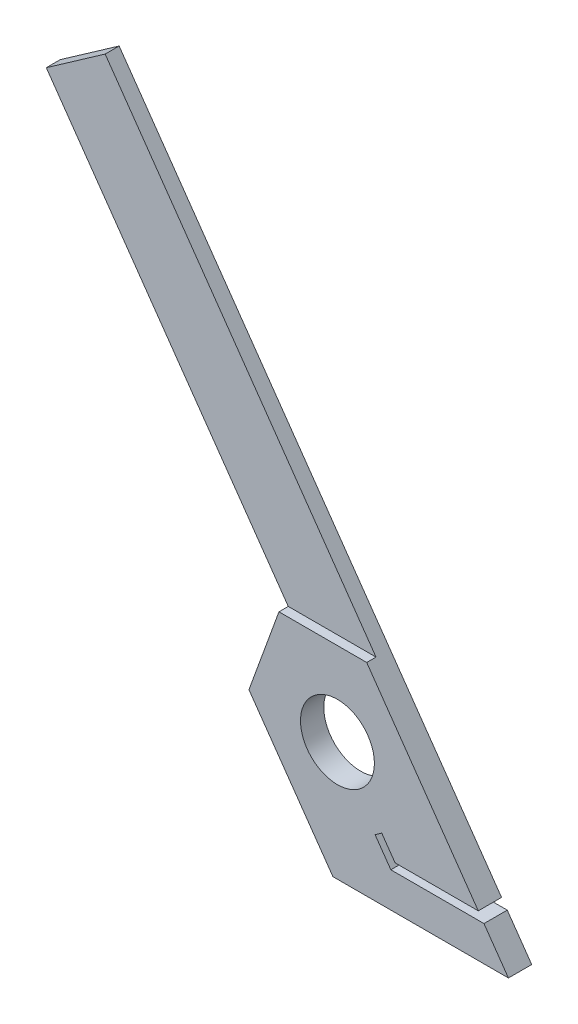
SolidWorks part; units mm, degrees
ref_plane "Front Plane" through (0, 0, 0) normal (0, 0, 1) x (1, 0, 0)
ref_plane "Top Plane" through (0, 0, 0) normal (0, 1, 0) x (1, 0, 0)
ref_plane "Right Plane" through (0, 0, 0) normal (1, 0, 0) x (0, 0, -1)
sketch "Sketch1" plane through (0, 0, 0) normal (0, 0, 1) x (1, 0, 0)
  line L0 (-0.3878, -10.212) -> (-7.6022, 0.0913)
  line L1 (-20.7527, 40.4037) -> (-25.8109, 36.8618)
  line L2 (-7.6022, 0.0913) -> (-5.024, 7.175)
  line L3 (-5.024, 7.175) -> (-25.8109, 36.8618)
  line L4 (-20.7527, 40.4037) -> (12.098, -6.512)
  line L5 (12.098, -6.512) -> (4.9526, -6.512)
  line L6 (14.6888, -10.212) -> (-0.3878, -10.212)
  line L7 (5.0583, 3.5418) -> (-5.0583, -3.5418) construction
  line L8 (4.5882, -7.212) -> (3.232, -5.2752)
  line L9 (4.5882, -7.212) -> (12.5882, -7.212)
  line L10 (3.232, -5.2752) -> (3.8054, -4.8737)
  line L11 (3.8054, -4.8737) -> (4.9526, -6.512)
  line L12 (4.9526, -6.512) -> (4.9526, -7.212) construction
  line L13 (4.9526, -6.512) -> (4.3792, -6.9135) construction
  line L14 (12.5882, -7.212) -> (14.6888, -10.212)
  circle A0 centre (0, 0) radius 3.175
  point P12 (0, 0)
  dimension "D1" = 6.35
  dimension "D6" = 45
  dimension "D3" = 3
  dimension "D5" = 4
  dimension "D10" = 3
  dimension "D2" = 55
  dimension "D4" = 125
  dimension "D7" = 0.7
  dimension "D8" = 2
  dimension "D9" = 3
  dimension "D11" = 8
extrude "Boss-Extrude1" add sketch "Sketch1" along normal blind 1.2
sketch "Sketch2" plane through (0, 0, 1.2) normal (0, 0, 1) x (1, 0, 0)
  line L0 (-5.024, 7.175) -> (2.5143, 7.175)
  line L12 (-0.3878, -10.212) -> (14.6888, -10.212)
  line L13 (14.6888, -10.212) -> (12.5882, -7.212)
  line L14 (12.5882, -7.212) -> (4.5882, -7.212)
  line L15 (4.5882, -7.212) -> (3.232, -5.2752)
  line L16 (3.232, -5.2752) -> (3.8054, -4.8737)
  line L17 (3.8054, -4.8737) -> (4.9526, -6.512)
  line L18 (4.9526, -6.512) -> (12.098, -6.512)
  line L19 (12.098, -6.512) -> (-20.7527, 40.4037)
  line L20 (-20.7527, 40.4037) -> (-25.8109, 36.8618)
  line L21 (-25.8109, 36.8618) -> (-5.024, 7.175)
  line L22 (-5.024, 7.175) -> (-7.6022, 0.0913)
  line L23 (-7.6022, 0.0913) -> (-0.3878, -10.212)
  line L24 (-0.3878, -10.212) -> (14.6888, -10.212)
  line L25 (14.6888, -10.212) -> (12.5882, -7.212)
  line L26 (12.5882, -7.212) -> (4.5882, -7.212)
  line L27 (4.5882, -7.212) -> (3.232, -5.2752)
  line L28 (3.232, -5.2752) -> (3.8054, -4.8737)
  line L29 (3.8054, -4.8737) -> (4.9526, -6.512)
  line L30 (4.9526, -6.512) -> (12.098, -6.512)
  line L31 (12.098, -6.512) -> (2.5143, 7.175)
  line L34 (-5.024, 7.175) -> (-7.6022, 0.0913)
  line L35 (-7.6022, 0.0913) -> (-0.3878, -10.212)
  circle A0 centre (0, 0) radius 3.175 construction
  circle A1 centre (0, 0) radius 3.175
  dimension "D1" = 0
extrude "Boss-Extrude2" add sketch "Sketch2" along normal blind 0.8
